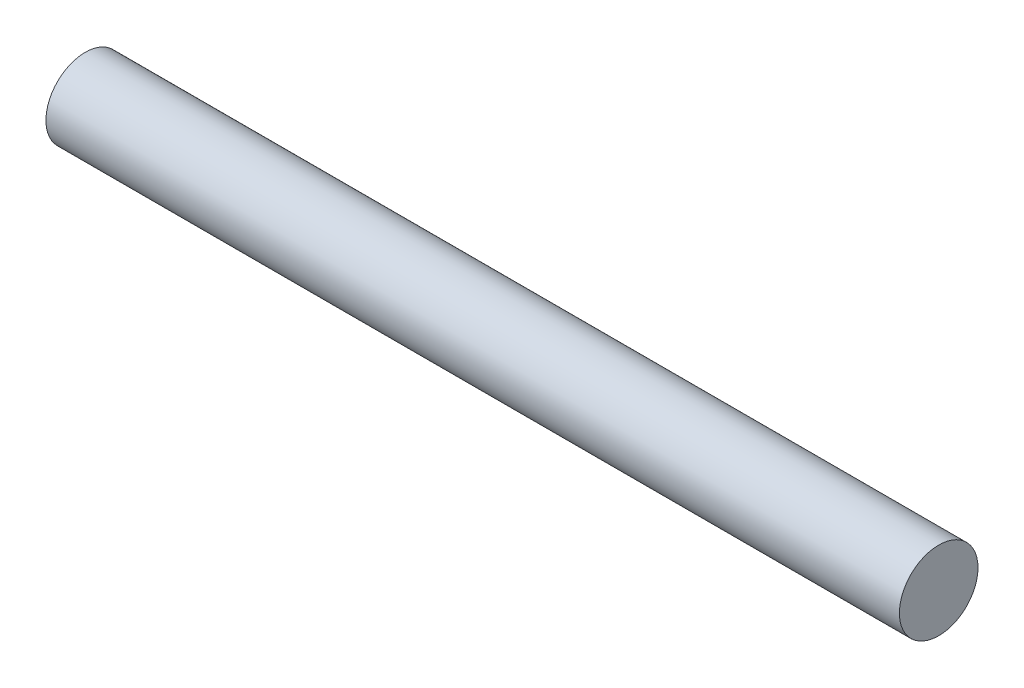
SolidWorks part; units mm, degrees
ref_plane "Front Plane" through (0, 0, 0) normal (0, 0, 1) x (1, 0, 0)
ref_plane "Top Plane" through (0, 0, 0) normal (0, 1, 0) x (1, 0, 0)
ref_plane "Right Plane" through (0, 0, 0) normal (1, 0, 0) x (0, 0, -1)
sketch "Sketch1" plane through (0, 0, 0) normal (0, 0, 1) x (1, 0, 0)
  line L0 (0, 0) -> (190, 0)
  dimension "D1" = 190
ref_plane "Plane1" through (0, 0, 0) normal (1, 0, 0) x (0, 0, -1)
sketch "Sketch12" plane through (0, 0, 0) normal (1, 0, 0) x (0, 0, -1)
  circle A0 centre (0, 0) radius 8.75
  dimension "D1" = 17.5
sweep "Sweep1" add profiles "Sketch12" path "Sketch1"
